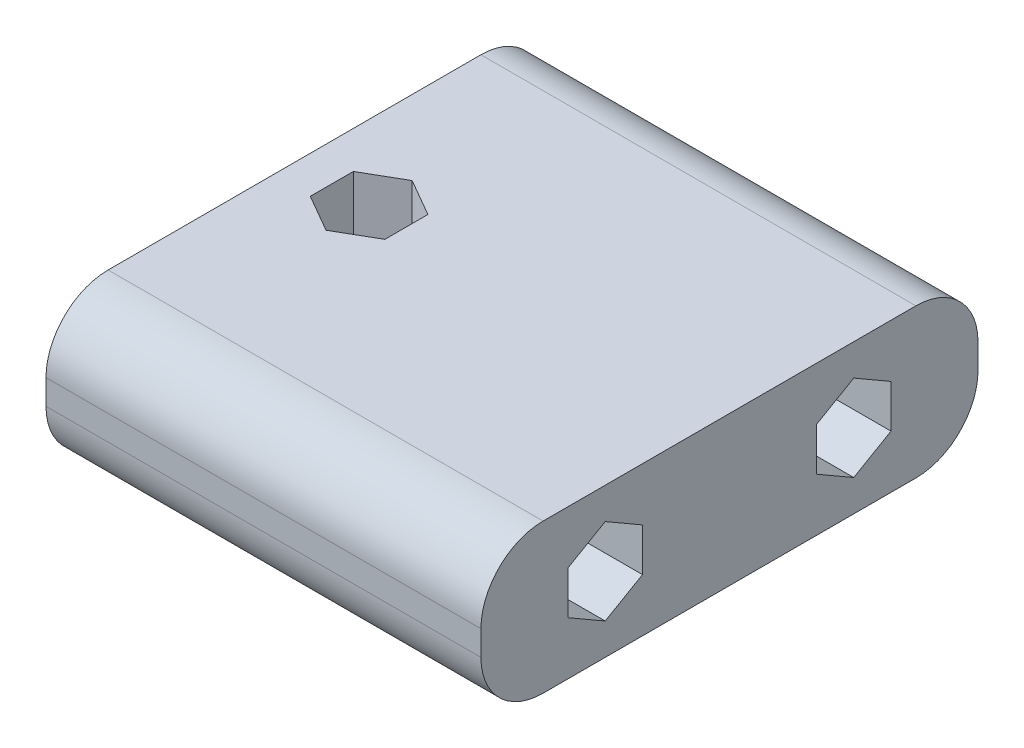
SolidWorks part; units mm, degrees
ref_plane "Front" through (0, 0, 0) normal (0, 0, 1) x (1, 0, 0)
ref_plane "Top" through (0, 0, 0) normal (0, 1, 0) x (1, 0, 0)
ref_plane "Right" through (0, 0, 0) normal (1, 0, 0) x (0, 0, -1)
sketch "草图2" plane through (0, 0, 0) normal (1, 0, 0) x (0, 0, -1)
  line L1 (0, 0) -> (40, 0)
  line L2 (0, 0) -> (0, 12)
  line L3 (0, 12) -> (40, 12)
  line L4 (40, 0) -> (40, 12)
  line L5 (10, 9.4641) -> (7, 7.7321)
  line L6 (7, 7.7321) -> (7, 4.2679)
  line L7 (7, 4.2679) -> (10, 2.5359)
  line L8 (10, 2.5359) -> (13, 4.2679)
  line L9 (13, 4.2679) -> (13, 7.7321)
  line L10 (13, 7.7321) -> (10, 9.4641)
  line L11 (30, 9.4641) -> (27, 7.7321)
  line L12 (27, 7.7321) -> (27, 4.2679)
  line L13 (27, 4.2679) -> (30, 2.5359)
  line L14 (30, 2.5359) -> (33, 4.2679)
  line L15 (33, 4.2679) -> (33, 7.7321)
  line L16 (33, 7.7321) -> (30, 9.4641)
  circle A0 centre (10, 6) radius 2 construction
  circle A1 centre (30, 6) radius 2 construction
  circle A2 centre (10, 6) radius 3 construction
  circle A3 centre (30, 6) radius 3 construction
  dimension "D3" = 4
  dimension "D4" = 4
  dimension "D1" = 40
  dimension "D2" = 12
  dimension "D5" = 6
  dimension "D6" = 10
  dimension "D7" = 20
  dimension "D8" = 6
  dimension "D9" = 6
extrude "凸台-拉伸1" add sketch "草图2" along normal blind 35
fillet "圆角1" radius 5 4 edges at (17.5, 0, -40) (17.5, 12, -40) (17.5, 0, 0) (17.5, 12, 0)
sketch "草图3" plane through (0, 0, 0) normal (0, -1, 0) x (1, 0, 0)
  line L0 (0, -20) -> (35, -20) construction
  line L1 (0, -5) -> (0, -35) construction
  line L2 (35, -5) -> (35, -35) construction
  line L4 (6, -16.5359) -> (3, -18.2679)
  line L5 (3, -18.2679) -> (3, -21.7321)
  line L6 (3, -21.7321) -> (6, -23.4641)
  line L7 (6, -23.4641) -> (9, -21.7321)
  line L8 (9, -21.7321) -> (9, -18.2679)
  line L9 (9, -18.2679) -> (6, -16.5359)
  circle A0 centre (6, -20) radius 2 construction
  circle A1 centre (6, -20) radius 3 construction
  dimension "D1" = 4
  dimension "D2" = 6
  dimension "D3" = 6
extrude "切除-拉伸1" cut sketch "草图3" against normal blind 20
sketch "草图4" plane through (0, 0, 0) normal (-1, 0, 0) x (0, 0, 1)
  line L0 (-30, 9.4641) -> (-27, 7.7321) construction
  line L1 (-27, 7.7321) -> (-27, 4.2679) construction
  line L2 (-27, 4.2679) -> (-30, 2.5359) construction
  line L3 (-30, 2.5359) -> (-33, 4.2679) construction
  line L4 (-33, 7.7321) -> (-30, 9.4641) construction
  line L5 (-33, 4.2679) -> (-33, 7.7321) construction
  line L6 (-30, 9.4641) -> (-27, 7.7321)
  line L7 (-27, 7.7321) -> (-27, 4.2679)
  line L8 (-27, 4.2679) -> (-30, 2.5359)
  line L9 (-30, 2.5359) -> (-33, 4.2679)
  line L10 (-33, 7.7321) -> (-30, 9.4641)
  line L11 (-33, 4.2679) -> (-33, 7.7321)
  line L12 (-7, 7.7321) -> (-7, 4.2679) construction
  line L13 (-10, 9.4641) -> (-7, 7.7321) construction
  line L14 (-7, 4.2679) -> (-10, 2.5359) construction
  line L15 (-10, 2.5359) -> (-13, 4.2679) construction
  line L16 (-13, 7.7321) -> (-10, 9.4641) construction
  line L17 (-13, 4.2679) -> (-13, 7.7321) construction
  line L18 (-7, 7.7321) -> (-7, 4.2679)
  line L19 (-10, 9.4641) -> (-7, 7.7321)
  line L20 (-7, 4.2679) -> (-10, 2.5359)
  line L21 (-10, 2.5359) -> (-13, 4.2679)
  line L22 (-13, 7.7321) -> (-10, 9.4641)
  line L23 (-13, 4.2679) -> (-13, 7.7321)
extrude "凸台-拉伸2" add sketch "草图4" against normal blind 10
